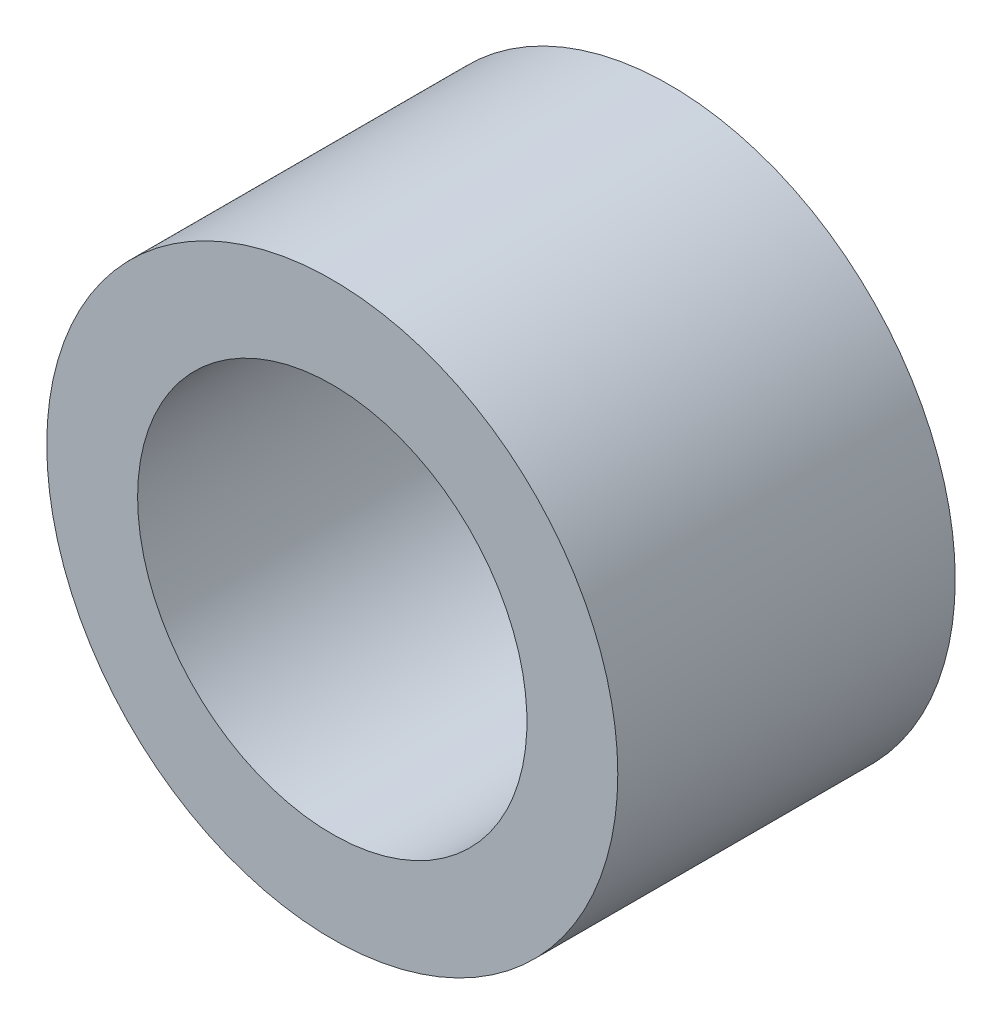
SolidWorks part; units mm, degrees
ref_plane "Front" through (0, 0, 0) normal (0, 0, 1) x (1, 0, 0)
ref_plane "Top" through (0, 0, 0) normal (0, 1, 0) x (1, 0, 0)
ref_plane "Right" through (0, 0, 0) normal (1, 0, 0) x (0, 0, -1)
sketch "草图1" plane through (0, 0, 0) normal (0, 0, 1) x (1, 0, 0)
  circle A0 centre (0, 0) radius 11
  circle A1 centre (0, 0) radius 7.5
  dimension "D1" = 15
  dimension "D2" = 22
extrude "凸台-拉伸1" add sketch "草图1" along normal blind 13
